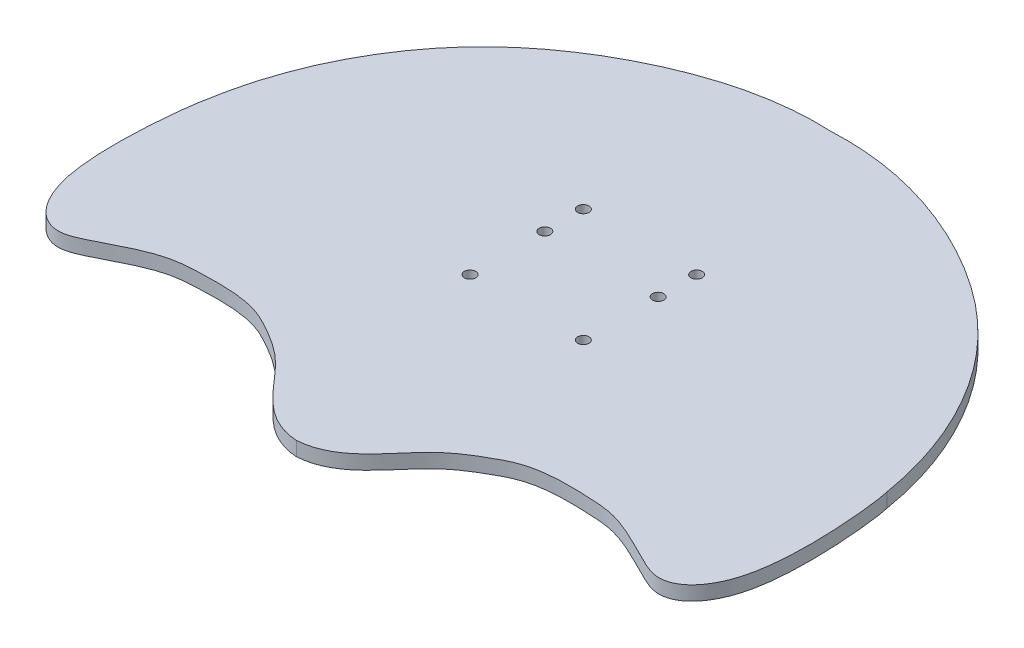
SolidWorks part; units mm, degrees
material "6061-T6 (SS)"
ref_plane "Front Plane" through (0, 0, 0) normal (0, 0, 1) x (1, 0, 0)
ref_plane "Top Plane" through (0, 0, 0) normal (0, 1, 0) x (1, 0, 0)
ref_plane "Right Plane" through (0, 0, 0) normal (1, 0, 0) x (0, 0, -1)
sketch "Sketch3" plane through (0, 0, 0) normal (0, 1, 0) x (1, 0, 0)
  line L0 (0, 0) -> (0, 159.1899) construction
  line L1 (0, 0) -> (0, -140.5301) construction
  line L2 (0, 0) -> (-190.5, 0) construction
  line L3 (0, 0) -> (190.5, 0) construction
  spline S0 degree 3 poles (-190.5, 0) (-184.3927, 37.537) (-157.2613, 93.9641) (-82.3875, 146.6227) (-31.3114, 160.7999) (0, 159.1899) knots 0 0 0 0 0.424401 0.65637 1 1 1 1
  spline S1 degree 3 poles (-190.5, 0) (-192.064, -4.9635) (-201.9672, -83.3146) (-174.6966, -109.29) (-151.6301, -100.568) (-131.4108, -87.7198) (-96.8436, -85.3754) (-78.6925, -86.2588) (-58.8335, -96.8794) (-37.3059, -109.9358) (-21.3496, -139.1148) (0, -140.5301) knots 0 0 0 0 0.166997 0.292321 0.319633 0.426735 0.458914 0.609242 0.64191 0.766802 1 1 1 1
  spline S2 degree 3 poles (190.5, 0) (192.064, -4.9635) (201.9672, -83.3146) (174.6966, -109.29) (151.6301, -100.568) (131.4108, -87.7198) (96.8436, -85.3754) (78.6925, -86.2588) (58.8335, -96.8794) (37.3059, -109.9358) (21.3496, -139.1148) (0, -140.5301) knots 0 0 0 0 0.166997 0.292321 0.319633 0.426735 0.458914 0.609242 0.64191 0.766802 1 1 1 1
  spline S3 degree 3 poles (190.5, 0) (184.3927, 37.537) (157.2613, 93.9641) (82.3875, 146.6227) (31.3114, 160.7999) (0, 159.1899) knots 0 0 0 0 0.424401 0.65637 1 1 1 1
  dimension "D1" = 381
  dimension "D2" = 299.72
  dimension "D3" = 159.1899
  dimension "D4" = 86.8953
  dimension "D5" = 104.4979
  dimension "D6" = 29.1616
  dimension "D7" = 92.2742
  dimension "D8" = 108.411
  dimension "D9" = 67.4883
  dimension "D10" = 43.7314
  dimension "D11" = 117.6915
  dimension "D12" = 162.2568
  dimension "D13" = 89.4522
  dimension "D14" = 140.1036
  dimension "D15" = 175.0666
  dimension "D16" = 50.2669
  dimension "D17" = 101.3666
  dimension "D18" = 138.1225
  dimension "D19" = 155.1557
  dimension "D20" = 192.0074
  dimension "D21" = 193.9268
  dimension "D23" = 76.6666
extrude "Boss-Extrude1" add sketch "Sketch3" along normal blind 7.9502 from surface at 0 starting at plane "Top Plane"
sketch "Sketch5" plane through (0, 0, 0) normal (0, -1, 0) x (1, 0, 0)
  line L0 (0, 0) -> (0, -20.32) construction
  line L1 (31.75, -52.07) -> (-31.75, -52.07)
  line L2 (31.75, -52.07) -> (31.75, 11.43)
  line L3 (31.75, 11.43) -> (-31.75, 11.43)
  line L4 (-31.75, -52.07) -> (-31.75, 11.43)
  line L5 (31.75, -52.07) -> (-31.75, 11.43) construction
  line L6 (31.75, 11.43) -> (-31.75, -52.07) construction
  line L7 (-31.75, -52.07) -> (-31.75, -30.48)
  line L8 (-31.75, -30.48) -> (31.75, -30.48) construction
  point P0 (0, -20.32)
  point P3 (0, -20.32)
  dimension "D2" = 63.5
  dimension "D3" = 63.5
  dimension "D4" = 21.59
hole_wizard "1/4 (0.25) Diameter Hole1" positions "Sketch6" profile "Sketch7" hole size "1/4" standard "ANSI Inch" end condition through all
sketch "Sketch6" plane through (0, 0, 0) normal (0, -1, 0) x (-1, 0, 0)
  point P0 (-31.75, 52.07)
  point P3 (31.75, 52.07)
  point P6 (31.75, -11.43)
  point P9 (-31.75, -11.43)
  point P12 (-31.75, 30.48)
  point P15 (31.75, 30.48)
sketch "Sketch7" plane through (31.75, 0, -52.07) normal (1, 0, 0) x (0, 0, -1)
  line L0 (0, 0) -> (0, 7.9502)
  line L1 (0, 7.9502) -> (3.175, 7.9502)
  line L2 (3.175, 7.9502) -> (3.175, 0)
  line L5 (3.175, 0) -> (0, 0)
  line L11 (0, -6.35) -> (0, 107.95) construction
  dimension "Thru Hole Dia." = 6.35
  dimension "Thru Hole Depth" = 7.9502
sketch "Sketch9" plane through (0, 7.9502, 0) normal (0, 1, 0) x (1, 0, 0)
  line L0 (102.3823, -86.0787) -> (102.3823, 130.9193)
  line L1 (-50.7649, -102.4301) -> (50.7649, -102.4301)
  spline S0 degree 3 poles (0, -140.5301) (21.3496, -139.1148) (37.3059, -109.9358) (58.8335, -96.8794) (78.6925, -86.2588) (96.8436, -85.3754) (131.4108, -87.7198) (151.6301, -100.568) (174.6966, -109.29) (201.9672, -83.3146) (192.064, -4.9635) (190.5, 0) knots 0 0 0 0 0.233198 0.35809 0.390758 0.541086 0.573265 0.680367 0.707679 0.833003 1 1 1 1 construction
  spline S1 degree 3 poles (190.5, 0) (184.3927, 37.537) (157.2613, 93.9641) (82.3875, 146.6227) (31.3114, 160.7999) (0, 159.1899) knots 0 0 0 0 0.424401 0.65637 1 1 1 1 construction
  spline S2 degree 3 poles (-190.5, 0) (-192.064, -4.9635) (-201.9672, -83.3146) (-174.6966, -109.29) (-151.6301, -100.568) (-131.4108, -87.7198) (-96.8436, -85.3754) (-78.6925, -86.2588) (-58.8335, -96.8794) (-37.3059, -109.9358) (-21.3496, -139.1148) (0, -140.5301) knots 0 0 0 0 0.166997 0.292321 0.319633 0.426735 0.458914 0.609242 0.64191 0.766802 1 1 1 1 construction
  dimension "D1" = 38.1
split line "Split Line1" [suppressed]
equation "\"Plate thickness\"=0.313"
equation "\"D1@Boss-Extrude1\"=\"Plate thickness\""
equation "\"Bracket Alignment\"= .80"
equation "\"D1@Sketch5\"=\"Bracket Alignment\""
